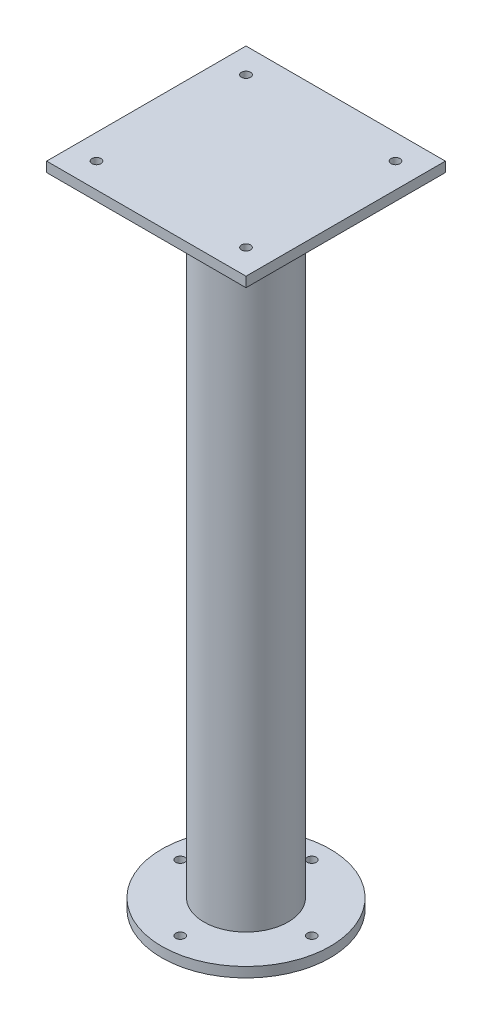
SolidWorks part; units mm, degrees
ref_plane "Front Plane" through (0, 0, 0) normal (0, 0, 1) x (1, 0, 0)
ref_plane "Top Plane" through (0, 0, 0) normal (0, 1, 0) x (1, 0, 0)
ref_plane "Right Plane" through (0, 0, 0) normal (1, 0, 0) x (0, 0, -1)
sketch "Sketch1" plane through (0, 0, 0) normal (0, 1, 0) x (1, 0, 0)
  circle A0 centre (0, 0) radius 66 construction
  circle A1 centre (0, 0) radius 84.5
  circle A2 centre (0, -66) radius 4.5
  circle A3 centre (66, 0) radius 4.5
  circle A4 centre (-66, 0) radius 4.5
  circle A5 centre (0, 66) radius 4.5
  dimension "D1" = 169
  dimension "D2" = 132
  dimension "D3" = 9
  dimension "D4" = 9
  dimension "D5" = 9
  dimension "D6" = 9
extrude "Boss-Extrude4" add sketch "Sketch1" along normal blind 10
sketch "Sketch2" plane through (0, 10, 0) normal (0, 1, 0) x (1, 0, 0)
  circle A0 centre (0, 0) radius 42.25
  dimension "D1" = 84.5
extrude "Boss-Extrude5" add sketch "Sketch2" along normal blind 630
sketch "Sketch4" plane through (0, 640, 0) normal (0, 1, 0) x (1, 0, 0)
  line L1 (-100, -100) -> (100, -100)
  line L2 (-100, -100) -> (-100, 100)
  line L3 (-100, 100) -> (100, 100)
  line L4 (100, -100) -> (100, 100)
  line L5 (-100, -100) -> (100, 100) construction
  line L6 (-100, 100) -> (100, -100) construction
  line L11 (-82.9569, -82.9569) -> (82.9569, 82.9569) construction
  line L12 (-82.9569, 82.9569) -> (82.9569, -82.9569) construction
  point P0 (0, 0)
  point P6 (0, 0)
  dimension "D1" = 200
  dimension "D2" = 200
extrude "Boss-Extrude6" add sketch "Sketch4" along normal blind 10
sketch "Sketch5" plane through (0, 650, 0) normal (0, 1, 0) x (1, 0, 0)
  line L1 (-75, -75) -> (75, -75)
  line L2 (-75, -75) -> (-75, 75)
  line L3 (-75, 75) -> (75, 75)
  line L4 (75, -75) -> (75, 75)
  line L5 (-75, -75) -> (75, 75) construction
  line L6 (-75, 75) -> (75, -75) construction
  circle A0 centre (75, -75) radius 4.5
  circle A1 centre (-75, -75) radius 4.5
  circle A2 centre (-75, 75) radius 4.5
  circle A3 centre (75, 75) radius 4.5
  point P0 (0, 0)
  dimension "D3" = 9
  dimension "D4" = 9
  dimension "D5" = 9
  dimension "D6" = 9
  dimension "D1" = 150
  dimension "D2" = 150
extrude "Cut-Extrude1" cut sketch "Sketch5" against normal through all contours L2 A1 L1 | L1 A1 L2 | L3 A2 L2 | L2 A2 L3 | L4 A3 L3 | L3 A3 L4 | L1 A0 L4 | L4 A0 L1
sketch "Sketch6" plane through (0, 0, 0) normal (0, 0, 1) x (1, 0, 0)
  line L0 (-100, 650) -> (100, 650) construction
  line L5 (110, 0) -> (-110, 0) construction
  point P0 (0, 650)
  point P3 (0, 0)
